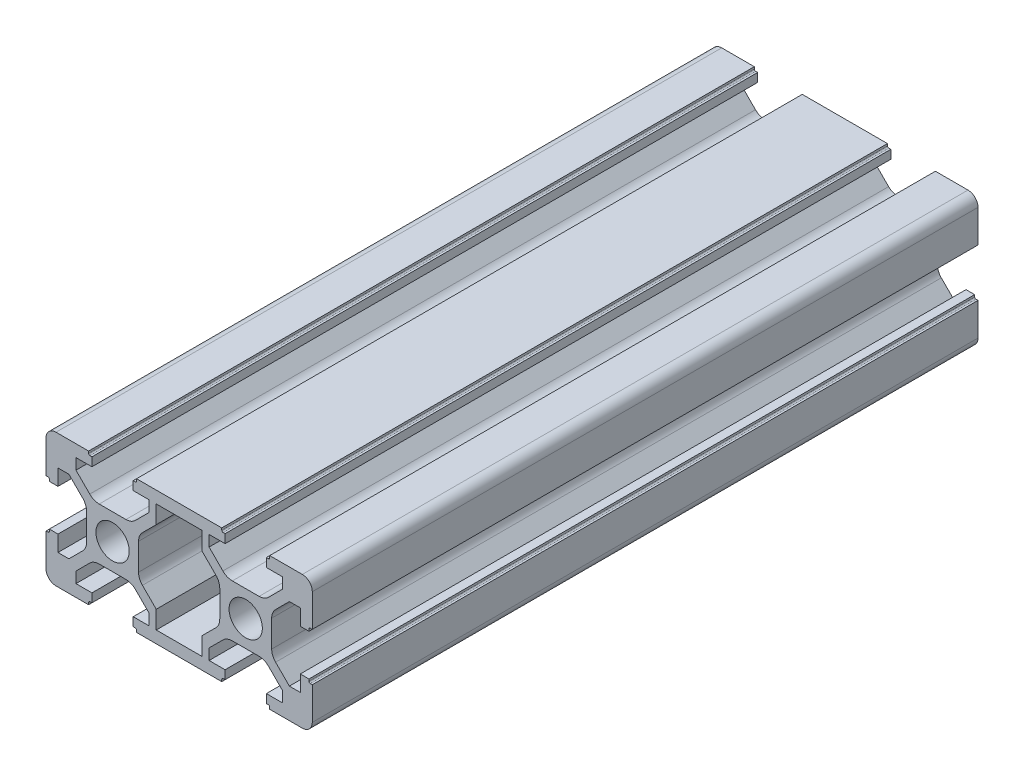
SolidWorks part; units mm, degrees
material "6063-T5"
ref_plane "Front Plane" through (0, 0, 0) normal (0, 0, 1) x (1, 0, 0)
ref_plane "Top Plane" through (0, 0, 0) normal (0, 1, 0) x (1, 0, 0)
ref_plane "Right Plane" through (0, 0, 0) normal (1, 0, 0) x (0, 0, -1)
sketch "Sketch2" plane through (0, 0, 0) normal (0, 0, 1) x (1, 0, 0)
  line L1 (-20, -10) -> (20, -10)
  line L2 (-20, -10) -> (-20, 10)
  line L3 (-20, 10) -> (20, 10)
  line L4 (20, -10) -> (20, 10)
  line L5 (-20, -10) -> (20, 10) construction
  line L6 (-20, 10) -> (20, -10) construction
  point P0 (0, 0)
  dimension "D1" = 40
  dimension "D2" = 20
extrude "Boss-Extrude1" add sketch "Sketch2" against normal blind 100
sketch "Sketch3" plane through (0, 0, 0) normal (0, 0, 1) x (1, 0, 0)
  line L0 (-10, -998.1953) -> (-10, 49001.8047) construction
  line L1 (0, -1000) -> (0, 49000) construction
  line L2 (10, -998.6632) -> (10, 49001.3368) construction
  line L3 (-1000, 0) -> (49000, 0) construction
  line L4 (-13.6, 10) -> (-6.4, 10)
  line L5 (-6.4, 10) -> (-6.4, 9.7)
  line L6 (-6.6, 9.5) -> (-6.9, 9.5)
  line L7 (-6.9, 9.5) -> (-6.9, 8.2)
  line L8 (-6.9, 8.2) -> (-4.5, 8.2)
  line L9 (-4.5, 8.2) -> (-4.5, 6.5607)
  line L10 (-4.5, 6.5607) -> (-6.5749, 4.4858)
  line L11 (-12.0109, 3.9) -> (-7.9891, 3.9)
  line L12 (-13.4251, 4.4858) -> (-15.5, 6.5607)
  line L13 (-15.5, 6.5607) -> (-15.5, 8.2)
  line L14 (-15.5, 8.2) -> (-13.1, 8.2)
  line L15 (-13.1, 8.2) -> (-13.1, 9.5)
  line L16 (-13.1, 9.5) -> (-13.4, 9.5)
  line L17 (-13.6, 10) -> (-13.6, 9.7)
  line L18 (20, 10) -> (-20, 10) construction
  line L19 (-717.1068, -707.1068) -> (34638.2323, 34648.2323) construction
  line L20 (-10, 10) -> (-10, 0) construction
  line L21 (-13.6, -10) -> (-13.6, -9.7)
  line L22 (-13.6, -10) -> (-6.4, -10)
  line L23 (-6.4, -10) -> (-6.4, -9.7)
  line L24 (-6.6, -9.5) -> (-6.9, -9.5)
  line L25 (-6.9, -9.5) -> (-6.9, -8.2)
  line L26 (-6.9, -8.2) -> (-4.5, -8.2)
  line L27 (-4.5, -8.2) -> (-4.5, -6.5607)
  line L28 (-4.5, -6.5607) -> (-6.5749, -4.4858)
  line L29 (-12.0109, -3.9) -> (-7.9891, -3.9)
  line L30 (-13.4251, -4.4858) -> (-15.5, -6.5607)
  line L31 (-15.5, -6.5607) -> (-15.5, -8.2)
  line L32 (-15.5, -8.2) -> (-13.1, -8.2)
  line L33 (-13.1, -8.2) -> (-13.1, -9.5)
  line L34 (-13.1, -9.5) -> (-13.4, -9.5)
  line L35 (13.6, -10) -> (6.4, -10)
  line L36 (6.4, -10) -> (6.4, -9.7)
  line L37 (6.6, -9.5) -> (6.9, -9.5)
  line L38 (6.9, -9.5) -> (6.9, -8.2)
  line L39 (6.9, -8.2) -> (4.5, -8.2)
  line L40 (4.5, -8.2) -> (4.5, -6.5607)
  line L41 (4.5, -6.5607) -> (6.5749, -4.4858)
  line L42 (12.0109, -3.9) -> (7.9891, -3.9)
  line L43 (13.4251, -4.4858) -> (15.5, -6.5607)
  line L44 (15.5, -6.5607) -> (15.5, -8.2)
  line L45 (15.5, -8.2) -> (13.1, -8.2)
  line L46 (13.1, -8.2) -> (13.1, -9.5)
  line L47 (13.1, -9.5) -> (13.4, -9.5)
  line L48 (13.6, -10) -> (13.6, -9.7)
  line L49 (13.6, 10) -> (13.6, 9.7)
  line L50 (13.6, 10) -> (6.4, 10)
  line L51 (6.4, 10) -> (6.4, 9.7)
  line L52 (6.6, 9.5) -> (6.9, 9.5)
  line L53 (6.9, 9.5) -> (6.9, 8.2)
  line L54 (6.9, 8.2) -> (4.5, 8.2)
  line L55 (4.5, 8.2) -> (4.5, 6.5607)
  line L56 (4.5, 6.5607) -> (6.5749, 4.4858)
  line L57 (12.0109, 3.9) -> (7.9891, 3.9)
  line L58 (13.4251, 4.4858) -> (15.5, 6.5607)
  line L59 (15.5, 6.5607) -> (15.5, 8.2)
  line L60 (15.5, 8.2) -> (13.1, 8.2)
  line L61 (13.1, 8.2) -> (13.1, 9.5)
  line L62 (13.1, 9.5) -> (13.4, 9.5)
  line L77 (-16.5607, -5.5) -> (-18.2, -5.5)
  line L78 (-16.5607, 5.5) -> (-14.4858, 3.4251)
  line L79 (-18.2, 3.1) -> (-18.2, 5.5)
  line L80 (-19.5, 3.4) -> (-19.5, 3.1)
  line L81 (-19.5, -3.1) -> (-19.5, -3.4)
  line L82 (-18.2, -5.5) -> (-18.2, -3.1)
  line L83 (-14.4858, -3.4251) -> (-16.5607, -5.5)
  line L84 (-13.9, -2.0109) -> (-13.9, 2.0109)
  line L85 (-20, -3.6) -> (-19.7, -3.6)
  line L86 (-18.2, 5.5) -> (-16.5607, 5.5)
  line L87 (-19.5, 3.1) -> (-18.2, 3.1)
  line L88 (-20, 3.6) -> (-19.7, 3.6)
  line L89 (-18.2, -3.1) -> (-19.5, -3.1)
  line L90 (-20, -3.6) -> (-20, 3.6)
  line L91 (-20, 10) -> (-20, -10) construction
  line L92 (14.4858, -3.4251) -> (16.5607, -5.5)
  line L93 (13.9, -2.0109) -> (13.9, 2.0109)
  line L94 (16.5607, 5.5) -> (14.4858, 3.4251)
  line L95 (18.2, 5.5) -> (16.5607, 5.5)
  line L96 (18.2, 3.1) -> (18.2, 5.5)
  line L97 (19.5, 3.1) -> (18.2, 3.1)
  line L98 (19.5, 3.4) -> (19.5, 3.1)
  line L99 (20, 3.6) -> (19.7, 3.6)
  line L100 (20, -3.6) -> (20, 3.6)
  line L101 (20, -3.6) -> (19.7, -3.6)
  line L102 (19.5, -3.1) -> (19.5, -3.4)
  line L103 (18.2, -3.1) -> (19.5, -3.1)
  line L104 (18.2, -5.5) -> (18.2, -3.1)
  line L105 (16.5607, -5.5) -> (18.2, -5.5)
  line L148 (-3.4393, 8.2) -> (-3.4393, 5.5)
  line L149 (-3.4393, 5.5) -> (-5.5142, 3.4251)
  line L150 (-3.4393, 8.2) -> (3.4393, 8.2)
  line L151 (3.4393, 8.2) -> (3.4393, 5.5)
  line L152 (3.4393, 5.5) -> (5.5142, 3.4251)
  line L153 (6.1, 2.0109) -> (6.1, -2.0109)
  line L154 (5.5142, -3.4251) -> (3.4393, -5.5)
  line L155 (3.4393, -5.5) -> (3.4393, -8.2)
  line L156 (3.4393, -8.2) -> (-3.4393, -8.2)
  line L157 (-3.4393, -8.2) -> (-3.4393, -5.5)
  line L158 (-3.4393, -5.5) -> (-5.5142, -3.4251)
  line L159 (-6.1, 2.0109) -> (-6.1, -2.0109)
  arc A0 (-13.4251, 4.4858) -> (-12.0109, 3.9) centre (-12.0109, 5.9) ccw
  arc A1 (-7.9891, 3.9) -> (-6.5749, 4.4858) centre (-7.9891, 5.9) ccw
  arc A2 (-6.6, 9.5) -> (-6.4, 9.7) centre (-6.6, 9.7) ccw
  arc A4 (-13.6, 9.7) -> (-13.4, 9.5) centre (-13.4, 9.7) ccw
  circle A5 centre (-10, 0) radius 2.5
  arc A7 (-6.6, -9.5) -> (-6.4, -9.7) centre (-6.6, -9.7) cw
  arc A8 (-7.9891, -3.9) -> (-6.5749, -4.4858) centre (-7.9891, -5.9) cw
  arc A9 (-13.4251, -4.4858) -> (-12.0109, -3.9) centre (-12.0109, -5.9) cw
  arc A10 (-13.6, -9.7) -> (-13.4, -9.5) centre (-13.4, -9.7) cw
  arc A11 (6.6, -9.5) -> (6.4, -9.7) centre (6.6, -9.7) ccw
  arc A12 (7.9891, -3.9) -> (6.5749, -4.4858) centre (7.9891, -5.9) ccw
  arc A13 (13.4251, -4.4858) -> (12.0109, -3.9) centre (12.0109, -5.9) ccw
  arc A14 (13.6, -9.7) -> (13.4, -9.5) centre (13.4, -9.7) ccw
  circle A15 centre (10, 0) radius 2.5
  arc A16 (6.6, 9.5) -> (6.4, 9.7) centre (6.6, 9.7) cw
  arc A17 (7.9891, 3.9) -> (6.5749, 4.4858) centre (7.9891, 5.9) cw
  arc A18 (13.4251, 4.4858) -> (12.0109, 3.9) centre (12.0109, 5.9) cw
  arc A19 (13.6, 9.7) -> (13.4, 9.5) centre (13.4, 9.7) cw
  arc A24 (-19.5, 3.4) -> (-19.7, 3.6) centre (-19.7, 3.4) ccw
  arc A25 (-14.4858, -3.4251) -> (-13.9, -2.0109) centre (-15.9, -2.0109) ccw
  arc A26 (-13.9, 2.0109) -> (-14.4858, 3.4251) centre (-15.9, 2.0109) ccw
  arc A27 (-19.7, -3.6) -> (-19.5, -3.4) centre (-19.7, -3.4) ccw
  arc A28 (14.4858, -3.4251) -> (13.9, -2.0109) centre (15.9, -2.0109) cw
  arc A29 (13.9, 2.0109) -> (14.4858, 3.4251) centre (15.9, 2.0109) cw
  arc A30 (19.5, 3.4) -> (19.7, 3.6) centre (19.7, 3.4) cw
  arc A31 (19.7, -3.6) -> (19.5, -3.4) centre (19.7, -3.4) cw
  arc A33 (-5.5142, 3.4251) -> (-6.1, 2.0109) centre (-4.1, 2.0109) ccw
  arc A35 (5.5142, 3.4251) -> (6.1, 2.0109) centre (4.1, 2.0109) cw
  arc A37 (6.1, -2.0109) -> (5.5142, -3.4251) centre (4.1, -2.0109) cw
  arc A39 (-5.5142, -3.4251) -> (-6.1, -2.0109) centre (-4.1, -2.0109) cw
  dimension "D7" = 45
  dimension "D11" = 0.2
  dimension "D12" = 2
  dimension "D13" = 5
  dimension "D21" = 2
  dimension "D22" = 0.2
  dimension "D23" = 2
  dimension "D1" = 20
  dimension "D2" = 10
  dimension "D3" = 6.2
  dimension "D4" = 7.2
  dimension "D5" = 1.8
  dimension "D6" = 6.1
  dimension "D8" = 11
  dimension "D9" = 0.75
  dimension "D10" = 0.5
  dimension "D14" = 7.2
  dimension "D15" = 0.5
  dimension "D16" = 1.8
  dimension "D17" = 6.1
  dimension "D18" = 6.2
  dimension "D19" = 11
  dimension "D20" = 0.75
  dimension "D24" = 0.75
  dimension "D25" = 1.5
extrude "Cut-Extrude1" cut sketch "Sketch3" against normal through all both and the other way through all
fillet "Fillet1" radius 1.5 4 edges at (-20, 10, -50) (-20, -10, -50) (20, -10, -50) (20, 10, -50)
